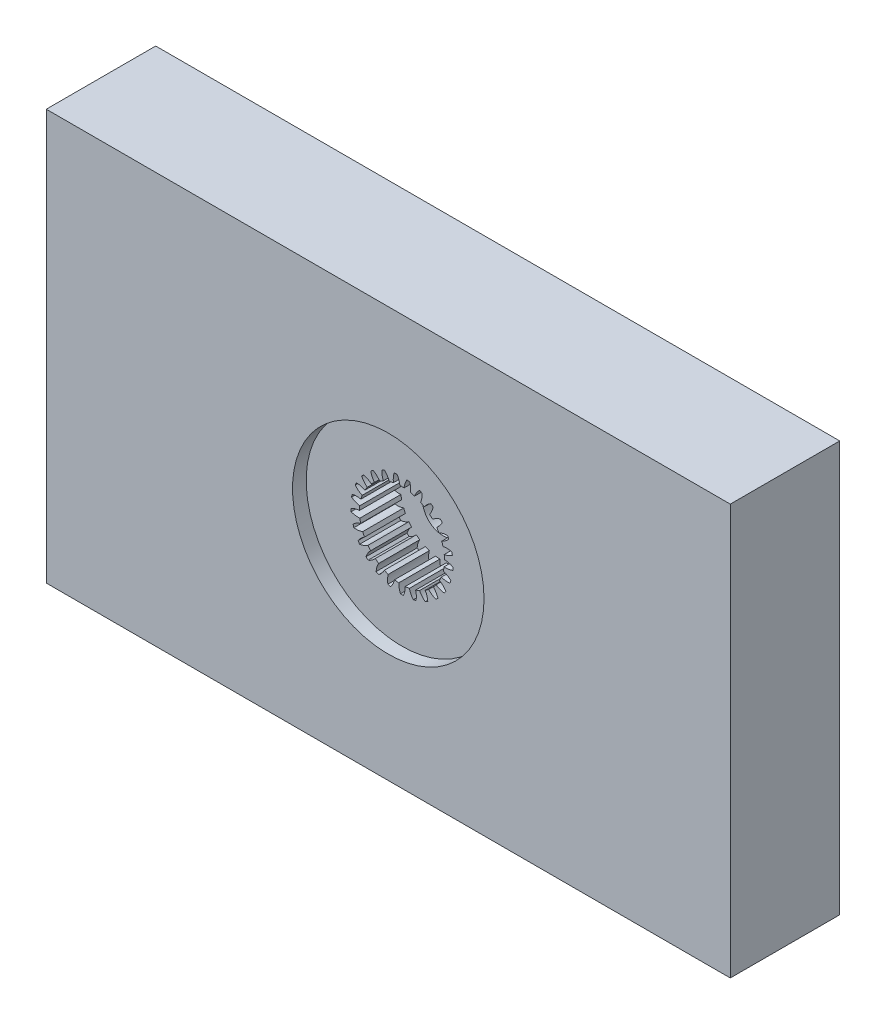
SolidWorks part; units mm, degrees
ref_plane "前视基准面" through (0, 0, 0) normal (0, 0, 1) x (1, 0, 0)
ref_plane "上视基准面" through (0, 0, 0) normal (0, 1, 0) x (1, 0, 0)
ref_plane "右视基准面" through (0, 0, 0) normal (1, 0, 0) x (0, 0, -1)
sketch "草图1" plane through (0, 0, 0) normal (0, 0, 1) x (1, 0, 0)
  line L0 (-46.2296, 25.125) -> (3.7704, 25.125)
  line L1 (-46.2296, 25.125) -> (-46.2296, -4.875)
  line L2 (3.7704, 25.125) -> (3.7704, -4.875)
  line L3 (-46.2296, -4.875) -> (3.7704, -4.875)
  line L4 (3.7704, 10.125) -> (-46.2296, 10.125) construction
  line L5 (-21.2296, 25.125) -> (-21.2296, -4.875) construction
  arc A0 (-19.9538, 13.6321) -> (-20.3072, 13.0938) centre (-19.0068, 12.6252) ccw
  arc A1 (-20.3072, 13.0938) -> (-20.6076, 13.171) centre (-21.2296, 10.125) ccw
  arc A2 (-20.6076, 13.171) -> (-20.658, 13.8129) centre (-21.9729, 13.3868) ccw
  arc A3 (-20.658, 13.8129) -> (-20.8661, 13.8391) centre (-21.2296, 10.125) ccw
  arc A4 (-20.8661, 13.8391) -> (-21.0745, 13.2299) centre (-19.6985, 13.0994) ccw
  arc A5 (-21.0745, 13.2299) -> (-21.3847, 13.2299) centre (-21.2296, 10.125) ccw
  arc A6 (-21.3847, 13.2299) -> (-21.5931, 13.8391) centre (-22.7607, 13.0994) ccw
  arc A7 (-21.5931, 13.8391) -> (-21.8012, 13.8129) centre (-21.2296, 10.125) ccw
  arc A8 (-21.8012, 13.8129) -> (-21.8515, 13.171) centre (-20.4863, 13.3868) ccw
  arc A9 (-21.8515, 13.171) -> (-22.152, 13.0938) centre (-21.2296, 10.125) ccw
  arc A10 (-22.152, 13.0938) -> (-22.5054, 13.6321) centre (-23.4523, 12.6252) ccw
  arc A11 (-22.5054, 13.6321) -> (-22.7003, 13.5549) centre (-21.2296, 10.125) ccw
  arc A12 (-22.7003, 13.5549) -> (-22.5895, 12.9206) centre (-21.3208, 13.4691) ccw
  arc A13 (-22.5895, 12.9206) -> (-22.8613, 12.7711) centre (-21.2296, 10.125) ccw
  arc A14 (-22.8613, 12.7711) -> (-23.3374, 13.2046) centre (-24.0043, 11.9939) ccw
  arc A15 (-23.3374, 13.2046) -> (-23.5071, 13.0813) centre (-21.2296, 10.125) ccw
  arc A16 (-23.5071, 13.0813) -> (-23.242, 12.4946) centre (-22.1496, 13.3414) ccw
  arc A17 (-23.242, 12.4946) -> (-23.4681, 12.2822) centre (-21.2296, 10.125) ccw
  arc A18 (-23.4681, 12.2822) -> (-24.0371, 12.5836) centre (-24.3819, 11.2451) ccw
  arc A19 (-24.0371, 12.5836) -> (-24.1708, 12.4221) centre (-21.2296, 10.125) ccw
  arc A20 (-24.1708, 12.4221) -> (-23.7681, 11.9196) centre (-22.9206, 13.0115) ccw
  arc A21 (-23.7681, 11.9196) -> (-23.9343, 11.6577) centre (-21.2296, 10.125) ccw
  arc A22 (-23.9343, 11.6577) -> (-24.5603, 11.8082) centre (-24.5614, 10.426) ccw
  arc A23 (-24.5603, 11.8082) -> (-24.6496, 11.6184) centre (-21.2296, 10.125) ccw
  arc A24 (-24.6496, 11.6184) -> (-24.1346, 11.232) centre (-23.5853, 12.5003) ccw
  arc A25 (-24.1346, 11.232) -> (-24.2305, 10.9369) centre (-21.2296, 10.125) ccw
  arc A26 (-24.2305, 10.9369) -> (-24.8743, 10.927) centre (-24.5316, 9.5879) ccw
  arc A27 (-24.8743, 10.927) -> (-24.9136, 10.721) centre (-21.2296, 10.125) ccw
  arc A28 (-24.9136, 10.721) -> (-24.3187, 10.4747) centre (-24.102, 11.8398) ccw
  arc A29 (-24.3187, 10.4747) -> (-24.3381, 10.1651) centre (-21.2296, 10.125) ccw
  arc A30 (-24.3381, 10.1651) -> (-24.9593, 9.9954) centre (-24.2943, 8.7836) ccw
  arc A31 (-24.9593, 9.9954) -> (-24.9461, 9.7861) centre (-21.2296, 10.125) ccw
  arc A32 (-24.9461, 9.7861) -> (-24.3086, 9.6955) centre (-24.4383, 11.0716) ccw
  arc A33 (-24.3086, 9.6955) -> (-24.2505, 9.3908) centre (-21.2296, 10.125) ccw
  arc A34 (-24.2505, 9.3908) -> (-24.8098, 9.0719) centre (-23.8645, 8.0636) ccw
  arc A35 (-24.8098, 9.0719) -> (-24.745, 8.8725) centre (-21.2296, 10.125) ccw
  arc A36 (-24.745, 8.8725) -> (-24.1051, 8.9433) centre (-24.5729, 10.2439) ccw
  arc A37 (-24.1051, 8.9433) -> (-23.973, 8.6626) centre (-21.2296, 10.125) ccw
  arc A38 (-23.973, 8.6626) -> (-24.4355, 8.2146) centre (-23.269, 7.4731) ccw
  arc A39 (-24.4355, 8.2146) -> (-24.3231, 8.0376) centre (-21.2296, 10.125) ccw
  arc A40 (-24.3231, 8.0376) -> (-23.7209, 8.2653) centre (-24.4974, 9.4087) ccw
  arc A41 (-23.7209, 8.2653) -> (-23.5231, 8.0263) centre (-21.2296, 10.125) ccw
  arc A42 (-23.5231, 8.0263) -> (-23.8597, 7.4774) centre (-22.5455, 7.0492) ccw
  arc A43 (-23.8597, 7.4774) -> (-23.7068, 7.3338) centre (-21.2296, 10.125) ccw
  arc A44 (-23.7068, 7.3338) -> (-23.1801, 7.7042) centre (-24.2166, 8.6185) ccw
  arc A45 (-23.1801, 7.7042) -> (-22.9291, 7.5218) centre (-21.2296, 10.125) ccw
  arc A46 (-22.9291, 7.5218) -> (-23.1186, 6.9065) centre (-21.7392, 6.8186) ccw
  arc A47 (-23.1186, 6.9065) -> (-22.9348, 6.8054) centre (-21.2296, 10.125) ccw
  arc A48 (-22.9348, 6.8054) -> (-22.5168, 7.2951) centre (-23.7482, 7.923) ccw
  arc A49 (-22.5168, 7.2951) -> (-22.2284, 7.181) centre (-21.2296, 10.125) ccw
  arc A50 (-22.2284, 7.181) -> (-22.2589, 6.5378) centre (-20.9009, 6.7957) ccw
  arc A51 (-22.2589, 6.5378) -> (-22.0557, 6.4856) centre (-21.2296, 10.125) ccw
  arc A52 (-22.0557, 6.4856) -> (-21.7726, 7.0639) centre (-23.1214, 7.3658) ccw
  arc A53 (-21.7726, 7.0639) -> (-21.4649, 7.0251) centre (-21.2296, 10.125) ccw
  arc A54 (-21.4649, 7.0251) -> (-21.3344, 6.3945) centre (-20.0833, 6.982) ccw
  arc A55 (-21.3344, 6.3945) -> (-21.1247, 6.3945) centre (-21.2296, 10.125) ccw
  arc A56 (-21.1247, 6.3945) -> (-20.9943, 7.0251) centre (-22.3758, 6.982) ccw
  arc A57 (-20.9943, 7.0251) -> (-20.6865, 7.0639) centre (-21.2296, 10.125) ccw
  arc A58 (-20.6865, 7.0639) -> (-20.4034, 6.4856) centre (-19.3377, 7.3658) ccw
  arc A59 (-20.4034, 6.4856) -> (-20.2003, 6.5378) centre (-21.2296, 10.125) ccw
  arc A60 (-20.2003, 6.5378) -> (-20.2308, 7.181) centre (-21.5582, 6.7957) ccw
  arc A61 (-20.2308, 7.181) -> (-19.9424, 7.2951) centre (-21.2296, 10.125) ccw
  arc A62 (-19.9424, 7.2951) -> (-19.5243, 6.8054) centre (-18.711, 7.923) ccw
  arc A63 (-19.5243, 6.8054) -> (-19.3405, 6.9065) centre (-21.2296, 10.125) ccw
  arc A64 (-19.3405, 6.9065) -> (-19.53, 7.5218) centre (-20.7199, 6.8186) ccw
  arc A65 (-19.53, 7.5218) -> (-19.279, 7.7042) centre (-21.2296, 10.125) ccw
  arc A66 (-19.279, 7.7042) -> (-18.7523, 7.3338) centre (-18.2425, 8.6185) ccw
  arc A67 (-18.7523, 7.3338) -> (-18.5995, 7.4774) centre (-21.2296, 10.125) ccw
  arc A68 (-18.5995, 7.4774) -> (-18.936, 8.0263) centre (-19.9137, 7.0492) ccw
  arc A69 (-18.936, 8.0263) -> (-18.7383, 8.2653) centre (-21.2296, 10.125) ccw
  arc A70 (-18.7383, 8.2653) -> (-18.136, 8.0376) centre (-17.9617, 9.4087) ccw
  arc A71 (-18.136, 8.0376) -> (-18.0237, 8.2146) centre (-21.2296, 10.125) ccw
  arc A72 (-18.0237, 8.2146) -> (-18.4862, 8.6626) centre (-19.1901, 7.4731) ccw
  arc A73 (-18.4862, 8.6626) -> (-18.3541, 8.9433) centre (-21.2296, 10.125) ccw
  arc A74 (-18.3541, 8.9433) -> (-17.7141, 8.8725) centre (-17.8863, 10.2439) ccw
  arc A75 (-17.7141, 8.8725) -> (-17.6493, 9.0719) centre (-21.2296, 10.125) ccw
  arc A76 (-17.6493, 9.0719) -> (-18.2087, 9.3908) centre (-18.5947, 8.0636) ccw
  arc A77 (-18.2087, 9.3908) -> (-18.1505, 9.6955) centre (-21.2296, 10.125) ccw
  arc A78 (-18.1505, 9.6955) -> (-17.5131, 9.7861) centre (-18.0209, 11.0716) ccw
  arc A79 (-17.5131, 9.7861) -> (-17.4999, 9.9954) centre (-21.2296, 10.125) ccw
  arc A80 (-17.4999, 9.9954) -> (-18.121, 10.1651) centre (-18.1648, 8.7836) ccw
  arc A81 (-18.121, 10.1651) -> (-18.1405, 10.4747) centre (-21.2296, 10.125) ccw
  arc A82 (-18.1405, 10.4747) -> (-17.5456, 10.721) centre (-18.3571, 11.8398) ccw
  arc A83 (-17.5456, 10.721) -> (-17.5848, 10.927) centre (-21.2296, 10.125) ccw
  arc A84 (-17.5848, 10.927) -> (-18.2287, 10.9369) centre (-17.9275, 9.5879) ccw
  arc A85 (-18.2287, 10.9369) -> (-18.3245, 11.232) centre (-21.2296, 10.125) ccw
  arc A86 (-18.3245, 11.232) -> (-17.8095, 11.6184) centre (-18.8738, 12.5003) ccw
  arc A87 (-17.8095, 11.6184) -> (-17.8988, 11.8082) centre (-21.2296, 10.125) ccw
  arc A88 (-17.8988, 11.8082) -> (-18.5249, 11.6577) centre (-17.8977, 10.426) ccw
  arc A89 (-18.5249, 11.6577) -> (-18.6911, 11.9196) centre (-21.2296, 10.125) ccw
  arc A90 (-18.6911, 11.9196) -> (-18.2884, 12.4221) centre (-19.5386, 13.0115) ccw
  arc A91 (-18.2884, 12.4221) -> (-18.4221, 12.5836) centre (-21.2296, 10.125) ccw
  arc A92 (-18.4221, 12.5836) -> (-18.991, 12.2822) centre (-18.0773, 11.2451) ccw
  arc A93 (-18.991, 12.2822) -> (-19.2171, 12.4946) centre (-21.2296, 10.125) ccw
  arc A94 (-19.2171, 12.4946) -> (-18.952, 13.0813) centre (-20.3095, 13.3414) ccw
  arc A95 (-18.952, 13.0813) -> (-19.1217, 13.2046) centre (-21.2296, 10.125) ccw
  arc A96 (-19.1217, 13.2046) -> (-19.5978, 12.7711) centre (-18.4549, 11.9939) ccw
  arc A97 (-19.5978, 12.7711) -> (-19.8697, 12.9206) centre (-21.2296, 10.125) ccw
  arc A98 (-19.8697, 12.9206) -> (-19.7588, 13.5549) centre (-21.1383, 13.4691) ccw
  arc A99 (-19.7588, 13.5549) -> (-19.9538, 13.6321) centre (-21.2296, 10.125) ccw
  dimension "D1" = 50
  dimension "D2" = 30
extrude "凸台-拉伸1" add sketch "草图1" along normal blind 8 contours L0 L1 L3 L2 | A0 A1 A2 A3 A4 A5 A6 A7 A8 A9 A10 A11 A12 A13 A14 A15 A16 A17 A18 A19 A20 A21 A22 A23 A24 A25 A26 A27 A28 A29 A30 A31 A32 A33 A34 A35 A36 A37 A38 A39 A40 A41 A42 A43 A44 A45 A46 A47 A48 A49 A50 A51 A52 A53 A54 A55 A56 A57 A58 A59 A60 A61 A62 A63 A64 A65 A66 A67 A68 A69 A70 A71 A72 A73 A74 A75 A76 A77 A78 A79 A80 A81 A82 A83 A84 A85 A86 A87 A88 A89 A90 A91 A92 A93 A94 A95 A96 A97 A98 A99
sketch "草图2" plane through (0, 0, 0) normal (0, 0, -1) x (-1, 0, 0)
  circle A0 centre (21.2296, 10.125) radius 3.7319
  circle A1 centre (21.2296, 10.125) radius 1.5
extrude "凸台-拉伸2" add sketch "草图2" against normal blind 4
sketch "草图3" plane through (0, 0, 0) normal (0, 0, -1) x (-1, 0, 0)
  circle A0 centre (21.2296, 10.125) radius 3
extrude "切除-拉伸1" cut sketch "草图3" against normal blind 1
draft "拔模1" type of draft neutral plane draft angle 1 faces to draft 1 face at (-24.2296, 10.125, 1) neutral plane through (-21.2296, 10.125, 1) neutral plane normal (0, 0, -1) parameters "D1"=1
sketch "草图4" plane through (0, 0, 8) normal (0, 0, 1) x (1, 0, 0)
  circle A0 centre (-21.2296, 10.125) radius 7
extrude "切除-拉伸2" cut sketch "草图4" against normal blind 1
